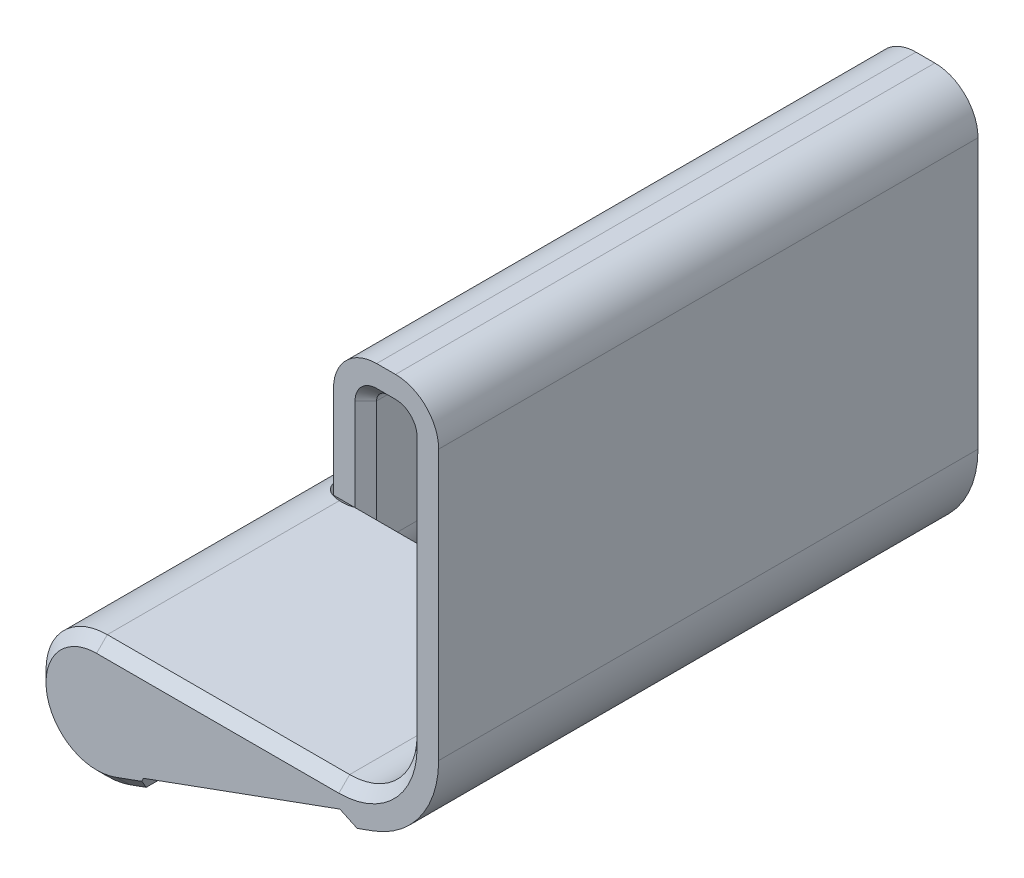
SolidWorks part; units mm, degrees
ref_plane "Front Plane" through (0, 0, 0) normal (0, 0, 1) x (1, 0, 0)
ref_plane "Top Plane" through (0, 0, 0) normal (0, 1, 0) x (1, 0, 0)
ref_plane "Right Plane" through (0, 0, 0) normal (1, 0, 0) x (0, 0, -1)
sketch "Sketch1" plane through (0, 0, 0) normal (0, 0, 1) x (1, 0, 0)
  line L0 (0, 0) -> (2.4, 0) construction
  line L1 (2.4, 0) -> (2.4, 9.2)
  line L2 (0, 0) -> (0, 9.2)
  line L3 (3.2, 10) -> (4.6, 10)
  line L4 (3.2, 12.4) -> (4.6, 12.4)
  line L5 (5.4, 9.2) -> (5.4, -10.8)
  line L6 (7.8, 9.2) -> (7.8, -10.8)
  line L7 (5.4, 9.2) -> (7.8, 9.2) construction
  line L8 (3.9, 10) -> (3.9, 12.4) construction
  line L9 (2.9309, -17.7537) -> (-15.8629, -24.5941)
  line L10 (0.4, -15.8) -> (-17.573, -15.8)
  line L11 (-3.2971, -3.9598) -> (-0.4686, -1.1314)
  line L12 (-3.2971, -3.9598) -> (-1.6, -5.6569)
  line L13 (-1.6, -5.6569) -> (1.2284, -2.8284)
  arc A0 (2.4, 9.2) -> (3.2, 10) centre (3.2, 9.2) cw
  arc A1 (4.6, 10) -> (5.4, 9.2) centre (4.6, 9.2) cw
  arc A2 (0, 9.2) -> (3.2, 12.4) centre (3.2, 9.2) cw
  arc A3 (4.6, 12.4) -> (7.8, 9.2) centre (4.6, 9.2) cw
  arc A4 (5.4, -10.8) -> (0.4, -15.8) centre (0.4, -10.8) cw
  arc A5 (7.8, -10.8) -> (2.9309, -17.7537) centre (0.4, -10.8) cw
  arc A6 (-15.8629, -24.5941) -> (-17.573, -24.8957) centre (-17.573, -19.8957) cw
  arc A7 (-17.573, -15.8) -> (-17.573, -24.8957) centre (-17.573, -20.3478) ccw
  arc A8 (0, 0) -> (-0.4686, -1.1314) centre (-1.6, 0) cw
  arc A9 (2.4, 0) -> (1.2284, -2.8284) centre (-1.6, 0) cw
  dimension "D1" = 0.8
  dimension "D6" = 5
  dimension "D9" = 5
  dimension "D11" = 1.6
  dimension "D2" = 2.4
  dimension "D3" = 10
  dimension "D4" = 3
  dimension "D5" = 70
  dimension "D7" = 20
  dimension "D8" = 20
  dimension "D10" = 45
  dimension "D12" = 4
extrude "Boss-Extrude1" add sketch "Sketch1" along normal blind 40
sketch "Sketch3" plane through (0, 0, 40) normal (0, 0, 1) x (1, 0, 0)
  line L0 (-14.0906, -22.8849) -> (0.4746, -17.5836)
  line L1 (0.4746, -17.5836) -> (1.7563, -18.1813)
  line L2 (1.7563, -18.1813) -> (-14.6883, -24.1666)
  line L3 (-14.6883, -24.1666) -> (-14.0906, -22.8849)
  line L5 (2.9309, -17.7537) -> (-15.8629, -24.5941) construction
  point P2 (-6.466, -21.1739)
  point P5 (-6.466, -21.1739)
  dimension "D1" = 15.5
  dimension "D2" = 1
extrude "Cut-Extrude2" cut sketch "Sketch3" against normal through all
sketch "Sketch4" plane through (6.0488, -16.6189, 0) normal (0.342, -0.9397, 0) x (0.9397, 0.342, 0)
  line L0 (-13.3179, 40) -> (-13.3179, 0) construction
  line L1 (-3.3179, 0) -> (-23.3179, 0) construction
  line L2 (-6.9013, 20) -> (-5.5679, 20) construction
  line L3 (-5.5679, 20) -> (-4.2346, 20) construction
  line L4 (-4.2346, 20) -> (-2.9013, 20) construction
  line L5 (-5.5679, 0) -> (-5.5679, 40) construction
  circle A0 centre (-4.9013, 20) radius 2
  circle A2 centre (-21.7346, 20) radius 2
  point P14 (-13.3179, 20)
  dimension "D1" = 4
extrude "Cut-Extrude3" cut sketch "Sketch4" against normal blind 10
chamfer "Chamfer2" distance 0.8 angle 45 12 edges at (-15.2756, -24.3804, 40) (-16.7048, -24.8197, 40) (-22.1208, -20.3478, 40) (-8.5865, -15.8, 40) (3.9355, -14.3355, 40) (2.4, 4.6, 40) (5.4, -0.8, 40) (2.6343, 9.7657, 40) (5.1657, 9.7657, 40) (3.9, 10, 40) (-0.1858, -4.2426, 40) (2.0955, -1.5307, 40)
sketch "Sketch2" plane through (2.4, 0, 0) normal (1, 0, 0) x (0, 0, -1)
  line L0 (-40, 2.3431) -> (-32, -5.6569)
  line L1 (-32, -5.6569) -> (-40, -5.6569)
  line L2 (-40, -5.6569) -> (-40, 2.3431)
  line L3 (-39.2, -5.6569) -> (0, -5.6569) construction
  line L4 (-40, 0) -> (-40, 9.2) construction
  line L5 (0, 2.3431) -> (-8, -5.6569)
  line L6 (-8, -5.6569) -> (0, -5.6569)
  line L7 (0, -5.6569) -> (0, 2.3431)
  dimension "D1" = 8
extrude "Cut-Extrude1" cut sketch "Sketch2" against normal through all
fillet "Fillet2" radius 0.8 2 edges at (-1.6, -5.6569, 20) (-3.2971, -3.9598, 20)
